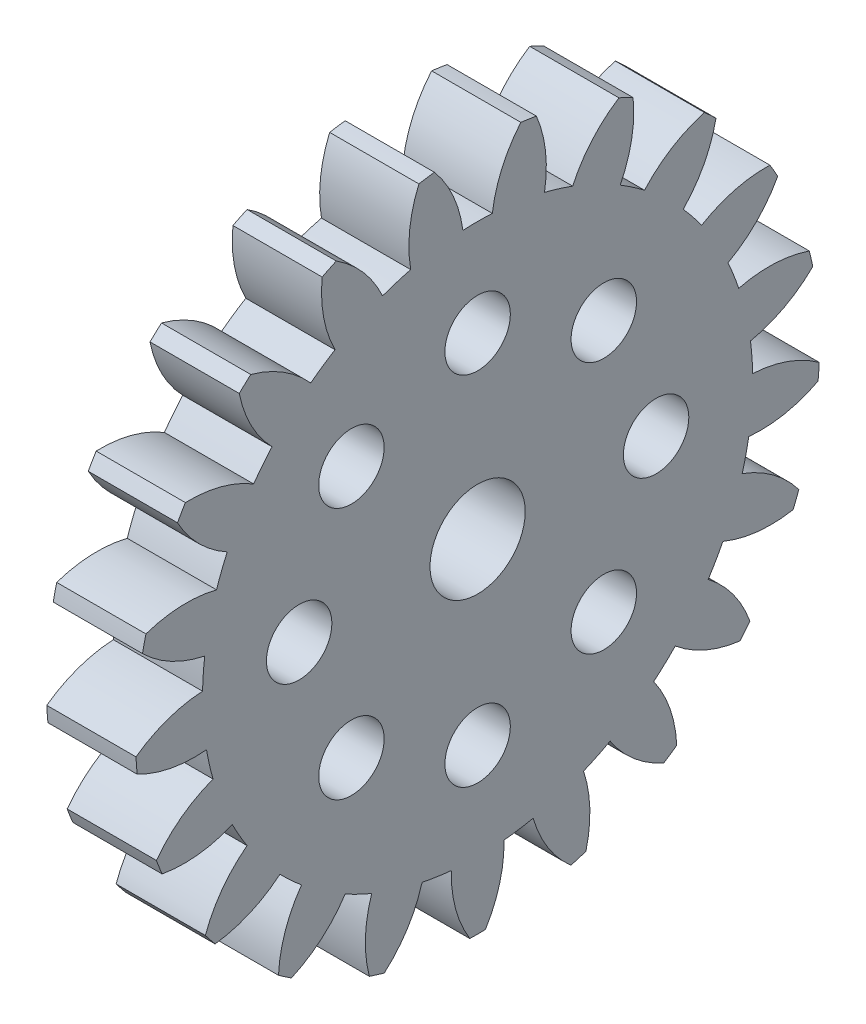
SolidWorks part; units mm, degrees
material "ﾎﾟﾘｵｷｼﾒﾁﾚﾝ(POM)ｱｾﾀｰﾙ共重合体"
ref_plane "Plane1" through (0, 0, 0) normal (0, 0, 1) x (1, 0, 0)
ref_plane "Plane2" through (0, 0, 0) normal (0, 1, 0) x (1, 0, 0)
ref_plane "Plane3" through (0, 0, 0) normal (1, 0, 0) x (0, 0, -1)
other "Configuration Table"
sketch "HoldingSke" plane through (0, 0, 0) normal (0, 1, 0) x (1, 0, 0)
  line L0 (0, 0) -> (0.9336, -0.3584)
  line L1 (-15, 0) -> (100, 0) construction
  line L2 (0, 0) -> (-2.1039, 2.3779)
  line L3 (0, 0) -> (-11.863, 4.5341)
  line L4 (0, 0) -> (8.0624, 3.0949)
  line L5 (0, 0) -> (-46.8476, -17.4728)
  line L6 (0, 0) -> (-2.4869, -1.6779)
  line L7 (-2.1039, 2.3779) -> (8.6586, 51.2059)
  line L8 (-76.2, 54.61) -> (-75.2, 54.61)
  line L9 (-71.009, 38.7566) -> (-53.1078, 45.2721)
  line L10 (-76.2, 71.12) -> (104.1128, 71.12)
  line L11 (0, 0) -> (-3, 0)
  line L12 (-76.2, 101.6) -> (-76.162, 101.6)
  line L13 (24.9733, 27.94) -> (52.9518, 28.4284)
  line L14 (24.9733, 27.94) -> (24.9743, 27.94)
  line L15 (24.9733, 27.94) -> (100.4006, 29.5858)
  line L16 (-63.627, -1) -> (-12.827, -1)
  circle A0 centre (0, 0) radius 4
  circle A1 centre (0, 0) radius 9.249
  circle A2 centre (0, 0) radius 37.5
  circle A3 centre (0, 0) radius 4
  dimension "MHD" = 18.498
  dimension "Hub_dia" = 75
  dimension "Bore" = 8
  dimension "MBD" = 8
  dimension "Num_teeth" = 21
  dimension "Pitch" = 1
  dimension "Overall_len" = 50
  dimension "Show_teeth" = 21
  dimension "Thickness" = 3
  dimension "OAL" = 50.0001
  dimension "T_dim" = 1
  dimension "Ap" = 20
  dimension "H" = 19.05
  dimension "Pitch_radius" = 180.3128
  dimension "Width" = 3
  dimension "Backlash" = 0.038
  dimension "Addendum_fac" = 1
  dimension "Dedendum_fac" = 1.25
  dimension "Clearance_fac" = 0.25
  dimension "Dedendum_add" = 0.001
  dimension "Module" = 1
sketch "BasProSke" plane through (0, 0, 0) normal (0, 1, 0) x (1, 0, 0)
  line L0 (-10, 0) -> (60, 0) construction
  line L1 (0, 0) -> (0, 11.5)
  line L2 (0, 0) -> (3, 0)
  line L3 (3, 0) -> (3, 11.5)
  line L4 (3, 11.5) -> (0, 11.5)
  dimension "Thickness" = 3
  dimension "Diameter" = 23
revolve "Base-Revolve" add sketch "BasProSke" angle 360 about L0
sketch "TooCutSke" plane through (0, 0, 0) normal (1, 0, 0) x (0, 0, -1)
  line L1 (0, 0) -> (0, 107) construction
  line L2 (0, 0) -> (-0.8511, 10.4654) construction
  line L3 (0, 0) -> (-3.1226, 20.7168) construction
  line L4 (-0.8511, 10.4654) -> (-1.5613, 10.3584) construction
  arc A0 (0.4953, 9.2357) -> (-0.4953, 9.2357) centre (0, 0) ccw
  arc A1 (1.4725, 11.431) -> (-1.4725, 11.431) centre (0, 0) ccw
  circle A2 centre (0, 0) radius 10.5 construction
  circle A3 centre (0, 0) radius 9.8668 construction
  arc A4 (-0.4953, 9.2357) -> (-1.4725, 11.431) centre (-4.6605, 8.6967) ccw
  arc A5 (1.4725, 11.431) -> (0.4953, 9.2357) centre (4.6605, 8.6967) ccw
  dimension "Root_dia" = 18.498
  dimension "Overcut_dia" = 23.0508
  dimension "Pitch_dia" = 21
  dimension "Base_dia" = 19.7335
  dimension "Flank_rad" = 4.2
  dimension "Half_ang" = 8.571
  dimension "Half_CT" = 0.7182
extrude "ToothCut" cut sketch "TooCutSke" along normal through all
fillet "Breaks" [suppressed] radius 0.02
fillet "RootFillets" [suppressed] radius 0.251
pattern_circular "TeethCuts" count 21 every 17.143 about axis through (-10, 0, 0) along (1, 0, 0) of "ToothCut", "RootFillets", "Breaks"
sketch "HubNeaOneSke" plane through (0, 0, 0) normal (-1, 0, 0) x (0, 0, 1)
  circle A0 centre (0, 0) radius 9.249
  dimension "Diameter" = 18.498
extrude "HubNearOne" [suppressed] add sketch "HubNeaOneSke" along normal blind 47.0001
sketch "HubNeaBotSke" plane through (0, 0, 0) normal (-1, 0, 0) x (0, 0, 1)
  circle A0 centre (0, 0) radius 9.249
  dimension "Diameter" = 18.498
extrude "HubNearBoth" [suppressed] add sketch "HubNeaBotSke" along normal blind 23.5
ref_plane "FarPln" through (3, 0, 0) normal (1, 0, 0) x (0, 0, -1)
sketch "HubFarSke" plane through (3, 0, 0) normal (1, 0, 0) x (0, 0, -1)
  circle A0 centre (0, 0) radius 9.249
  dimension "Diameter" = 18.498
extrude "HubFar" [suppressed] add sketch "HubFarSke" along normal blind 23.5
sketch "BorSke" plane through (0, 0, 0) normal (1, 0, 0) x (0, 0, -1)
  circle A0 centre (0, 0) radius 4
  dimension "Diameter" = 8
extrude "Bore" cut sketch "BorSke" along normal mid plane 100.0001
sketch "KeySke" plane through (0, 0, 0) normal (1, 0, 0) x (0, 0, -1)
  line L0 (-1, 0) -> (-1, 5)
  line L1 (-1, 5) -> (1, 5)
  line L2 (1, 5) -> (1, 0)
  line L3 (0, 0) -> (0, 34) construction
  line L4 (-1, 0) -> (1, 0)
  dimension "Offset" = 5
  dimension "Width" = 2
extrude "Keyway" [suppressed] cut sketch "KeySke" along normal mid plane 100.0001
pattern_circular "Keyway2" [suppressed] count 2 every 90 about axis through (-10, 0, 0) along (1, 0, 0)
sketch "ｽｹｯﾁ1" plane through (0, 0, 0) normal (-1, 0, 0) x (0, 0, 1)
  circle A0 centre (0, 0) radius 4 construction
  circle A1 centre (0, 0) radius 4
extrude "ﾎﾞｽ - 押し出し1" add sketch "ｽｹｯﾁ1" against normal up to surface (3 mm away) up to face at (3, 0, 4)
sketch "ｽｹｯﾁ2" plane through (3, 0, 0) normal (1, 0, 0) x (0, 0, -1)
  circle A0 centre (0, 0) radius 1.6
  circle A1 centre (0, 0) radius 6 construction
  circle A2 centre (6, 0) radius 1.1
  circle A3 centre (4.2426, -4.2426) radius 1.1
  circle A4 centre (0, -6) radius 1.1
  circle A5 centre (-4.2426, -4.2426) radius 1.1
  circle A6 centre (-6, 0) radius 1.1
  circle A7 centre (-4.2426, 4.2426) radius 1.1
  circle A8 centre (0, 6) radius 1.1
  circle A9 centre (4.2426, 4.2426) radius 1.1
  point P23 (0, 0)
  dimension "D1" = 2.2
  dimension "D2" = 12
  dimension "D3" = 3.2
extrude "ｶｯﾄ - 押し出し1" cut sketch "ｽｹｯﾁ2" against normal through all
equation "' \"Module@HoldingSke\" = 6.35"
equation "' \"Num_teeth@HoldingSke\" = 12"
equation "' \"Ap@HoldingSke\" =  20"
equation "' \"Ap@HoldingSke\" = 20"
equation "' \"Width@HoldingSke\" = 0.5 * 25.4"
equation "' \"Hub_dia@HoldingSke\"= 1 * 25.4"
equation "' \"Hub_dia@HoldingSke\" = 1 * 25.4"
equation "' \"Overall_len@HoldingSke\" = 1.0 * 25.4"
equation "' \"Bore@HoldingSke\" = 0.75 * 25.4"
equation "' \"T_dim@HoldingSke\" = 0.1 * 25.4"
equation "' \"Width@KeySke\" = 0.25 * 25.4"
equation "' \"Show_teeth@HoldingSke\" = 13"
equation "' \"Backlash@HoldingSke\" = 0.009 * 25.4"
equation "' \"Addendum_fac@HoldingSke\" = 1.0"
equation "' \"Dedendum_fac@HoldingSke\" = 1.25"
equation "' \"Dedendum_add@HoldingSke\" = 0.00005 * 25.4"
equation "' \"Clearance_fac@HoldingSke\" = 0.25"
equation "\"Pitch@HoldingSke\" = 1 / \"Module@HoldingSke\""
equation "\"Overcut_dia@TooCutSke\" = (\"Num_teeth@HoldingSke\" + 2 * \"Addendum_fac@HoldingSke\") / \"Pitch@HoldingSke\" + 0.002 * 25.4"
equation "\"Pitch_dia@TooCutSke\" = \"Num_teeth@HoldingSke\" / \"Pitch@HoldingSke\""
equation "\"Base_dia@TooCutSke\" = \"Num_teeth@HoldingSke\" / \"Pitch@HoldingSke\" * cos((\"Ap@HoldingSke\"  * 3.14159265 / 180))"
equation "\"Root_dia@TooCutSke\" = (\"Num_teeth@HoldingSke\" + 2) / \"Pitch@HoldingSke\" - 2 * (\"Addendum_fac@HoldingSke\" + \"Dedendum_fac@HoldingSke\") / \"Pitch@HoldingSke\" - \"Dedendum_add@HoldingSke\" * 2"
equation "\"Half_ang@TooCutSke\" = 180 / \"Num_teeth@HoldingSke\""
equation "\"Half_CT@TooCutSke\" = \"Num_teeth@HoldingSke\" / \"Pitch@HoldingSke\" * sin((3.14159265 / 2 / \"Num_teeth@HoldingSke\")) / 2 - 7 * \"Backlash@HoldingSke\" / 4"
equation "\"Flank_rad@TooCutSke\" = \"Num_teeth@HoldingSke\" / \"Pitch@HoldingSke\" / 5"
equation "\"Radius@RootFillets\" = \"Clearance_fac@HoldingSke\" / \"Pitch@HoldingSke\" + \"Dedendum_add@HoldingSke\""
equation "\"Break_rad@Breaks\" = 0.02 / \"Pitch@HoldingSke\""
equation "\"Thickness@HoldingSke\" = \"Width@HoldingSke\""
equation "\"OAL@HoldingSke\" = \"Thickness@HoldingSke\""
equation "\"MHD@HoldingSke\" = (\"Num_teeth@HoldingSke\" + 2) / \"Pitch@HoldingSke\" - 2 * (\"Addendum_fac@HoldingSke\" + \"Dedendum_fac@HoldingSke\")  / \"Pitch@HoldingSke\" - \"Dedendum_add@HoldingSke\" * 2"
equation "\"MBD@HoldingSke\" = (\"Num_teeth@HoldingSke\" + 2) / \"Pitch@HoldingSke\" - 2 * (\"Addendum_fac@HoldingSke\" + \"Dedendum_fac@HoldingSke\")  / \"Pitch@HoldingSke\" - \"Dedendum_add@HoldingSke\" * 2 - 0.002 * 25.4"
equation "\"MHD@HoldingSke\" = ((sgn( \"MHD@HoldingSke\" - \"Hub_dia@HoldingSke\" )-1)*( \"MHD@HoldingSke\" - \"Hub_dia@HoldingSke\" ))/-2+ \"Hub_dia@HoldingSke\""
equation "\"MBD@HoldingSke\" = ((sgn( \"MBD@HoldingSke\" - \"Bore@HoldingSke\" )-1)*( \"MBD@HoldingSke\" - \"Bore@HoldingSke\" ))/-2+ \"Bore@HoldingSke\""
equation "\"OAL@HoldingSke\" = ((sgn( \"OAL@HoldingSke\" - \"Overall_len@HoldingSke\" )+1)*( \"OAL@HoldingSke\" - \"Overall_len@HoldingSke\" ))/2 + \"Overall_len@HoldingSke\" + 0.000002 * 25.4"
equation "\"Num_teeth@TeethCuts\" = int( \"Show_teeth@HoldingSke\" ) + 1"
equation "\"Num_teeth@TeethCuts\" = ((sgn( \"Num_teeth@TeethCuts\" - \"Num_teeth@HoldingSke\" )-1)*( \"Num_teeth@TeethCuts\" - \"Num_teeth@HoldingSke\" ))/-2+ \"Num_teeth@HoldingSke\""
equation "\"Num_teeth@TeethCuts\" = ((sgn( \"Num_teeth@TeethCuts\" - 2.0)+1)*( \"Num_teeth@TeethCuts\" - 2.0))/2 +2.0"
equation "\"Angle@TeethCuts\" = 360.0 / \"Num_teeth@HoldingSke\""
equation "\"Diameter@BasProSke\" = (\"Num_teeth@HoldingSke\" + 2 * \"Addendum_fac@HoldingSke\") / \"Pitch@HoldingSke\""
equation "\"Thickness@BasProSke\"  = \"Thickness@HoldingSke\""
equation "' \"Fillet_rad@BasProSke\" =  \"Thickness@HoldingSke\" * 0.05"
equation "' \"Fillet_rad@BasProSke\" = \"Thickness@HoldingSke\" * 0.05"
equation "\"MHD@HoldingSke\" = ((sgn( \"MHD@HoldingSke\" - \"Root_dia@TooCutSke\" )-1)*( \"MHD@HoldingSke\" - \"Root_dia@TooCutSke\" ))/-2+ \"Root_dia@TooCutSke\""
equation "\"Diameter@HubNeaOneSke\" = \"MHD@HoldingSke\""
equation "\"Length@HubNearOne\" = \"OAL@HoldingSke\" - \"Thickness@BasProSke\""
equation "\"Diameter@HubNeaBotSke\" = \"MHD@HoldingSke\""
equation "\"Length@HubNearBoth\" = ( \"OAL@HoldingSke\" - \"Thickness@BasProSke\" ) / 2.0"
equation "\"Thickness@FarPln\" = \"Thickness@BasProSke\""
equation "\"Diameter@HubFarSke\" = \"MHD@HoldingSke\""
equation "\"Length@HubFar\" = ( \"OAL@HoldingSke\" - \"Thickness@BasProSke\" ) / 2.0"
equation "\"Diameter@BorSke\" = \"MBD@HoldingSke\""
equation "\"D1@Bore\" = \"OAL@HoldingSke\" * 2.0"
equation "\"D1@Keyway\" = \"OAL@HoldingSke\" * 2.0"
equation "\"Offset@KeySke\" = \"T_dim@HoldingSke\" + \"MBD@HoldingSke\" / 2.0"
